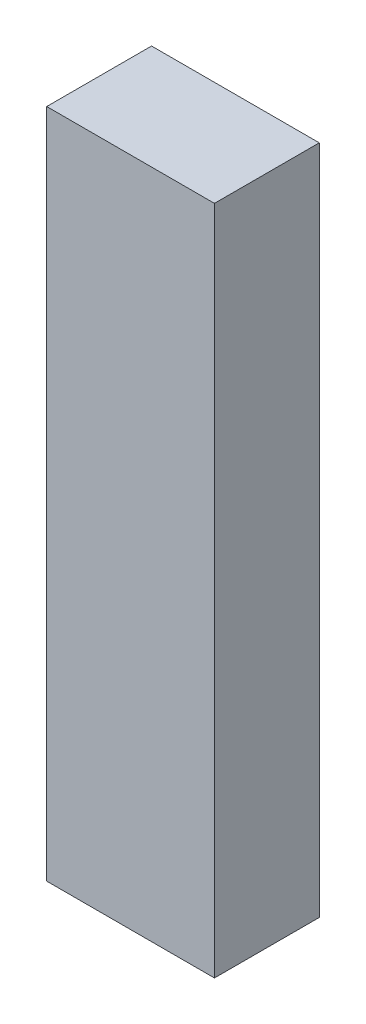
SolidWorks part; units mm, degrees
ref_plane "前视基准面" through (0, 0, 0) normal (0, 0, 1) x (1, 0, 0)
ref_plane "上视基准面" through (0, 0, 0) normal (0, 1, 0) x (1, 0, 0)
ref_plane "右视基准面" through (0, 0, 0) normal (1, 0, 0) x (0, 0, -1)
other "Configuration Table"
sketch "草图1" plane through (0, 0, 0) normal (0, 0, 1) x (1, 0, 0)
  line L1 (-16, -64) -> (16, -64)
  line L2 (-16, -64) -> (-16, 64)
  line L3 (-16, 64) -> (16, 64)
  line L4 (16, -64) -> (16, 64)
extrude "凸台-拉伸1" add sketch "草图1" against normal blind 20
